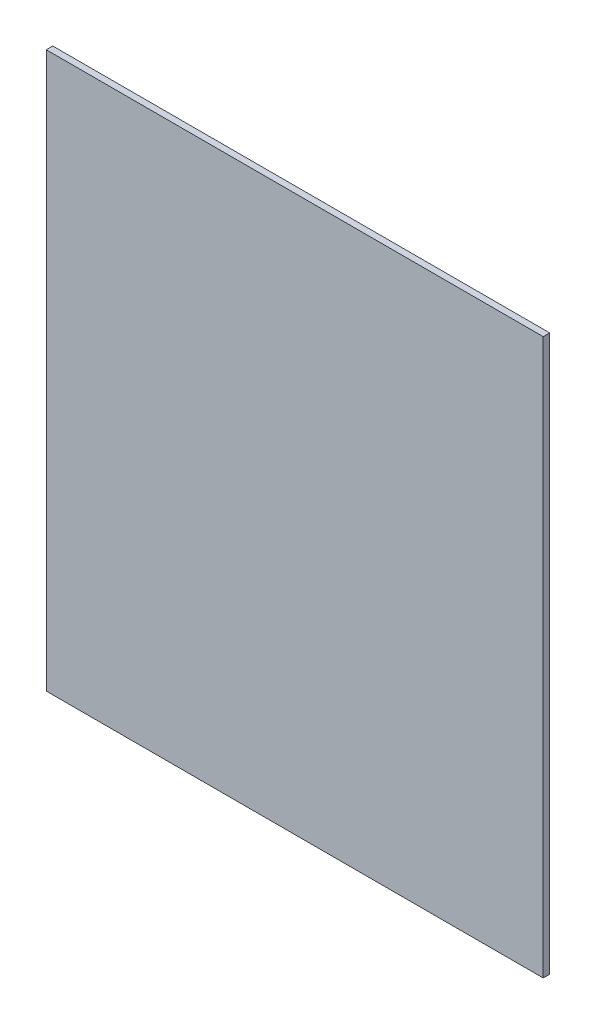
SolidWorks part; units mm, degrees
ref_plane "Front Plane" through (0, 0, 0) normal (0, 0, 1) x (1, 0, 0)
ref_plane "Top Plane" through (0, 0, 0) normal (0, 1, 0) x (1, 0, 0)
ref_plane "Right Plane" through (0, 0, 0) normal (1, 0, 0) x (0, 0, -1)
sketch "Sketch1" plane through (0, 0, 0) normal (0, 0, 1) x (1, 0, 0)
  line L1 (-76.5, -85.5) -> (76.5, -85.5)
  line L2 (-76.5, -85.5) -> (-76.5, 85.5)
  line L3 (-76.5, 85.5) -> (76.5, 85.5)
  line L4 (76.5, -85.5) -> (76.5, 85.5)
  line L5 (-76.5, -85.5) -> (76.5, 85.5) construction
  line L6 (-76.5, 85.5) -> (76.5, -85.5) construction
  point P0 (0, 0)
  dimension "D1" = 153
  dimension "D2" = 171
extrude "Boss-Extrude1" add sketch "Sketch1" along normal blind 2
